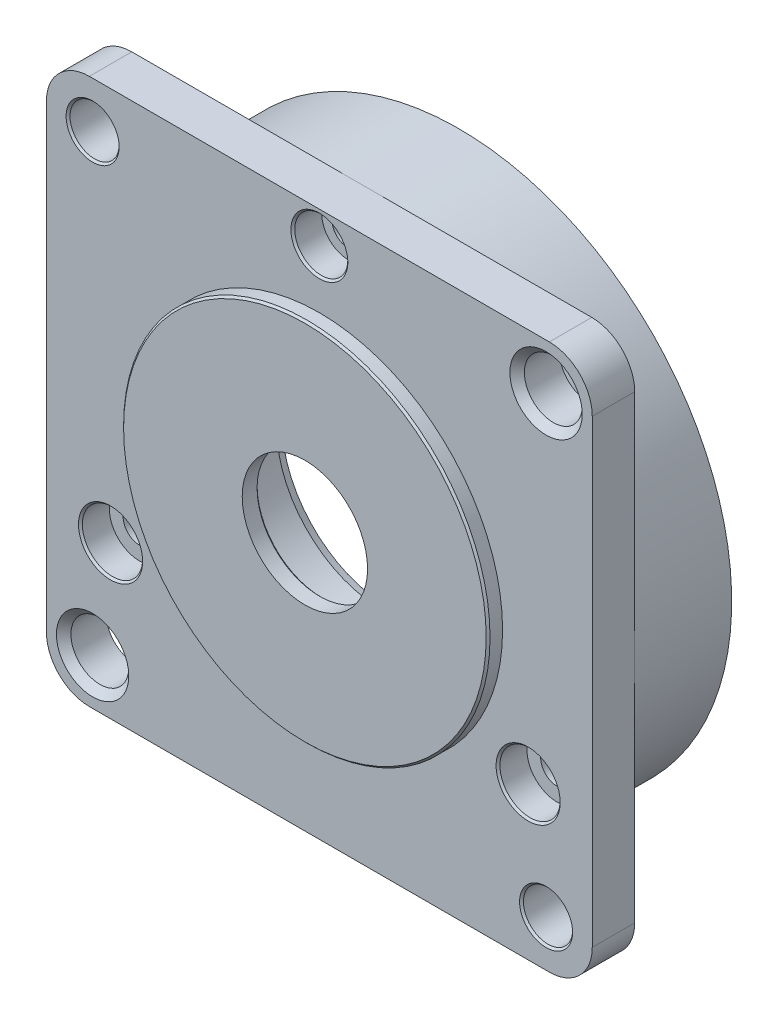
SolidWorks part; units mm, degrees
ref_plane "Ön Düzlem" through (0, 0, 0) normal (0, 0, 1) x (1, 0, 0)
ref_plane "Üst Düzlem" through (0, 0, 0) normal (0, 1, 0) x (1, 0, 0)
ref_plane "Sağ Düzlem" through (0, 0, 0) normal (1, 0, 0) x (0, 0, -1)
sketch "Çizim1" plane through (0, 0, 0) normal (0, 0, 1) x (1, 0, 0)
  line L1 (-23.85, 28.3) -> (23.85, 28.3)
  line L2 (-28.3, 23.85) -> (-28.3, -23.85)
  line L3 (-23.85, -28.3) -> (23.85, -28.3)
  line L4 (28.3, 23.85) -> (28.3, -23.85)
  line L5 (-28.3, 28.3) -> (28.3, -28.3) construction
  line L6 (-28.3, -28.3) -> (28.3, 28.3) construction
  arc A0 (23.85, 28.3) -> (28.3, 23.85) centre (23.85, 23.85) cw
  arc A1 (-23.85, 28.3) -> (-28.3, 23.85) centre (-23.85, 23.85) ccw
  arc A2 (-28.3, -23.85) -> (-23.85, -28.3) centre (-23.85, -23.85) ccw
  arc A3 (23.85, -28.3) -> (28.3, -23.85) centre (23.85, -23.85) ccw
  circle A4 centre (-23.5113, 23.5113) radius 2.55
  circle A5 centre (23.5113, -23.5113) radius 2.55
  circle A6 centre (-23.5113, -23.5113) radius 3
  circle A7 centre (23.5113, 23.5113) radius 3
  circle A8 centre (0, 0) radius 6.5
  circle A9 centre (0, 25) radius 1.7
  circle A10 centre (21.6506, -12.5) radius 1.7
  circle A11 centre (-21.6506, -12.5) radius 1.7
  point P0 (0, 0)
  point P38 (0, 0)
  dimension "D3" = 4.45
  dimension "D4" = 5.1
  dimension "D5" = 5.1
  dimension "D8" = 66.5
  dimension "D10" = 6
  dimension "D11" = 6
  dimension "D12" = 13
  dimension "D13" = 3.4
  dimension "D1" = 56.6
  dimension "D2" = 56.6
  dimension "D6" = 66.5
  dimension "D7" = 33.25
  dimension "D9" = 33.25
  dimension "D14" = 25
  dimension "D15" = 3
extrude "Yükseklik-Ekstrüzyon1" add sketch "Çizim1" along normal blind 4.4
sketch "Çizim2" plane through (0, 0, 4.4) normal (0, 0, 1) x (1, 0, 0)
  circle A0 centre (0, 0) radius 6.5 construction
  circle A1 centre (0, 0) radius 6.5
  circle A2 centre (0, 0) radius 19
  dimension "D1" = 38
extrude "Yükseklik-Ekstrüzyon2" add sketch "Çizim2" along normal blind 1.5
chamfer "Pah1" distance 0.2 angle 45 1 edges at (19, 0, 5.9)
chamfer "Pah2" distance 0.75 angle 45 2 edges at (26.5113, 23.5113, 4.4) (-20.5113, -23.5113, 4.4)
sketch "Çizim3" plane through (0, 0, 4.4) normal (0, 0, 1) x (1, 0, 0)
  circle A0 centre (-21.6506, -12.5) radius 3.125
  circle A1 centre (21.6506, -12.5) radius 3.125
  circle A2 centre (0, 25) radius 2.75
  circle A3 centre (0, 25) radius 1.7 construction
  circle A4 centre (21.6506, -12.5) radius 1.7 construction
  circle A5 centre (-21.6506, -12.5) radius 1.7 construction
  circle A6 centre (0, 25) radius 1.7
  circle A7 centre (21.6506, -12.5) radius 1.7
  circle A8 centre (-21.6506, -12.5) radius 1.7
  dimension "D1" = 6.25
  dimension "D2" = 5.5
extrude "Kes-Ekstrüzyon1" cut sketch "Çizim3" against normal blind 3
chamfer "Pah3" distance 0.2 angle 45 5 edges at (26.0613, -23.5113, 4.4) (-20.9613, 23.5113, 4.4) (2.75, 25, 4.4) (-18.5256, -12.5, 4.4) (24.7756, -12.5, 4.4)
sketch "Çizim4" plane through (0, 0, 0) normal (0, 0, -1) x (-1, 0, 0)
  circle A0 centre (0, 0) radius 11
  dimension "D1" = 22
extrude "Kes-Ekstrüzyon2" cut sketch "Çizim4" against normal blind 3.66
sketch "Çizim5" plane through (0, 0, 3.66) normal (0, 0, -1) x (-1, 0, 0)
  circle A0 centre (0, 0) radius 8.9
  dimension "D1" = 17.8
extrude "Kes-Ekstrüzyon3" cut sketch "Çizim5" against normal blind 0.5
chamfer "Pah4" distance 0.2 angle 45 1 edges at (-6.5, 0, 4.16)
sketch "Çizim6" plane through (0, 0, 0) normal (0, 0, -1) x (-1, 0, 0)
  circle A0 centre (0, 0) radius 12.75
  circle A1 centre (0, 0) radius 11 construction
  circle A2 centre (0, 0) radius 11
  dimension "D1" = 25.5
extrude "Yükseklik-Ekstrüzyon3" add sketch "Çizim6" along normal blind 2.9
chamfer "Pah5" distance 0.2 angle 75 1 edges at (-11, 0, -2.9)
sketch "Çizim7" plane through (0, 0, 0) normal (0, 0, -1) x (-1, 0, 0)
  circle A0 centre (0, 0) radius 26.75
  circle A1 centre (0, 0) radius 28.3
  dimension "D1" = 53.5
  dimension "D2" = 56.6
extrude "Yükseklik-Ekstrüzyon4" add sketch "Çizim7" along normal blind 10.06
sketch "Çizim8" plane through (0, 0, 0) normal (0, 0, -1) x (-1, 0, 0)
  line L0 (-2.9, 25) -> (-2.9, 26.5923)
  line L1 (2.9, 25) -> (2.9, 26.5923)
  line L2 (23.1006, -9.9885) -> (24.4796, -10.7847)
  line L3 (20.2006, -15.0115) -> (21.5796, -15.8076)
  line L4 (-20.2006, -15.0115) -> (-21.5796, -15.8076)
  line L5 (-23.1006, -9.9885) -> (-24.4796, -10.7847)
  circle A0 centre (0, 0) radius 12.75 construction
  circle A1 centre (0, 0) radius 26.75 construction
  circle A2 centre (0, 0) radius 12.75
  arc A3 (-2.9, 26.5923) -> (-24.4796, -10.7847) centre (0, 0) ccw
  arc A4 (-2.9, 25) -> (2.9, 25) centre (0, 25) ccw
  arc A6 (23.1006, -9.9885) -> (20.2006, -15.0115) centre (21.6506, -12.5) ccw
  arc A7 (-20.2006, -15.0115) -> (-23.1006, -9.9885) centre (-21.6506, -12.5) ccw
  arc A8 (-21.5796, -15.8076) -> (21.5796, -15.8076) centre (0, 0) ccw
  arc A9 (24.4796, -10.7847) -> (2.9, 26.5923) centre (0, 0) ccw
  point P24 (0, 0)
  dimension "D1" = 5.8
  dimension "D2" = 3
extrude "Kes-Ekstrüzyon4" cut sketch "Çizim8" against normal blind 0.5
sketch "Çizim10" plane through (0, 0, -10.06) normal (0, 0, -1) x (-1, 0, 0)
  circle A0 centre (0, 0) radius 27.5
  dimension "D1" = 55
extrude "Kes-Ekstrüzyon5" cut sketch "Çizim10" against normal blind 1.5
